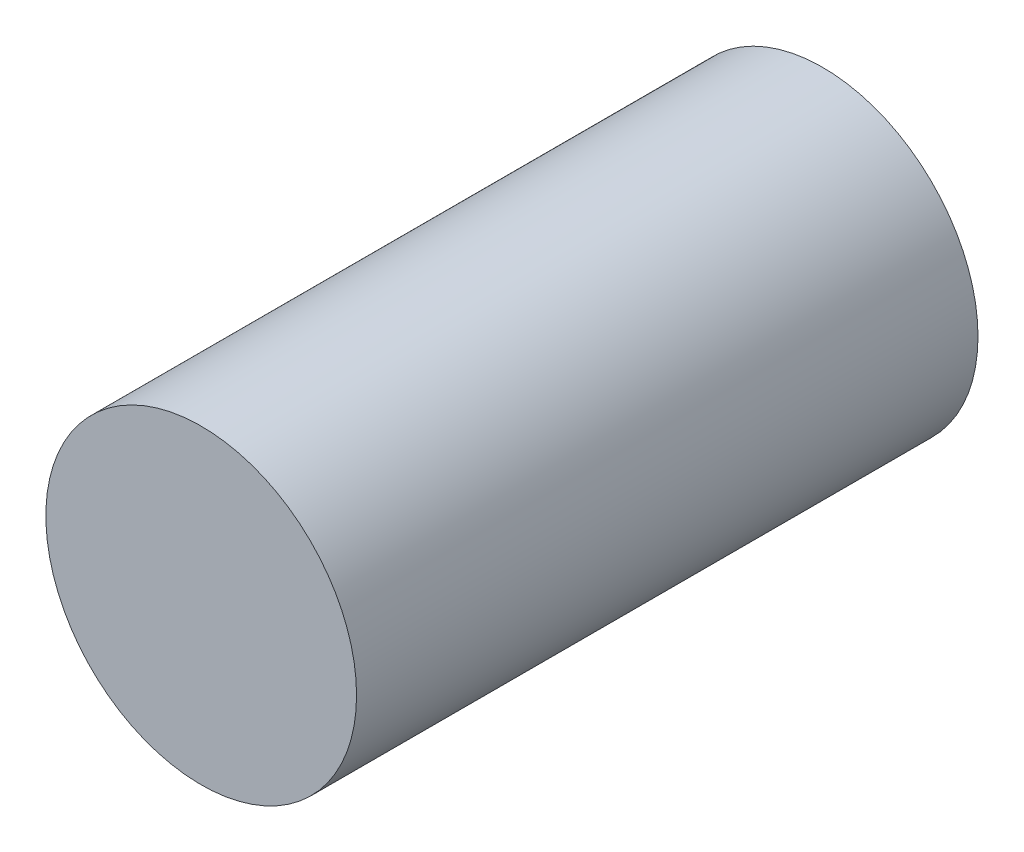
SolidWorks part; units mm, degrees
material "Cobre"
ref_plane "Alzado" through (0, 0, 0) normal (0, 0, 1) x (1, 0, 0)
ref_plane "Planta" through (0, 0, 0) normal (0, 1, 0) x (1, 0, 0)
ref_plane "Vista lateral" through (0, 0, 0) normal (1, 0, 0) x (0, 0, -1)
sketch "Croquis1" plane through (0, 0, 0) normal (0, 0, 1) x (1, 0, 0)
  circle A0 centre (0, 0) radius 7.5
  dimension "D1" = 15
extrude "Saliente-Extruir1" add sketch "Croquis1" along normal blind 30
